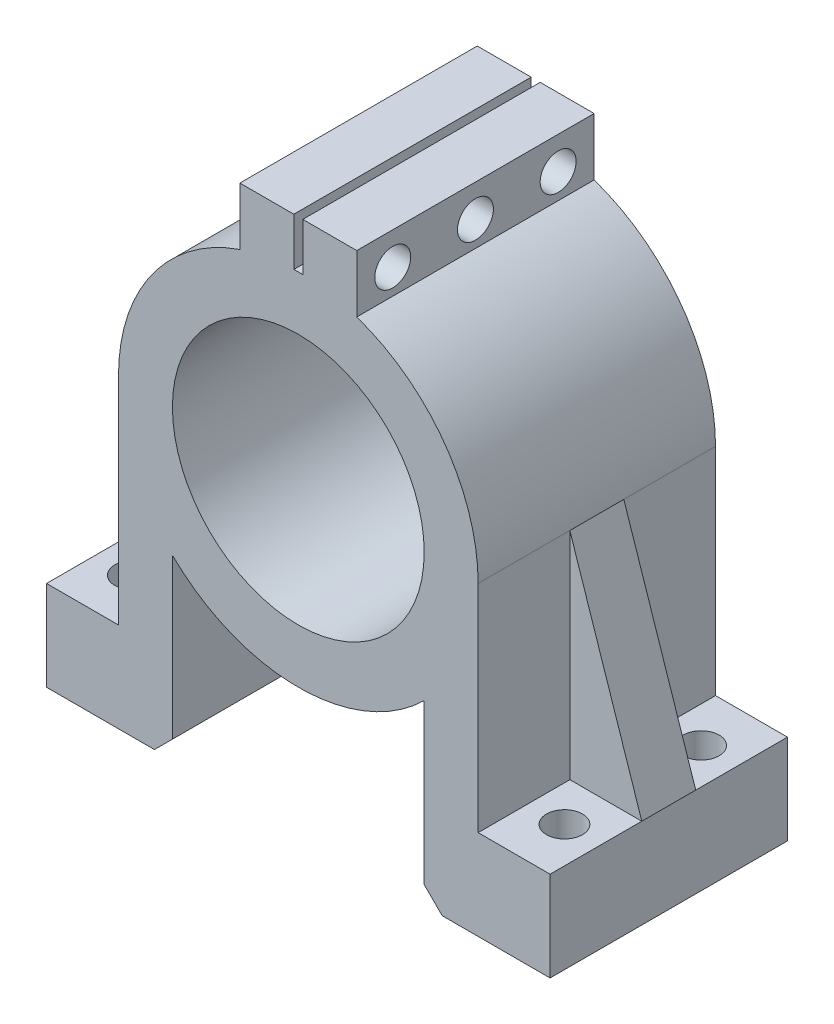
SolidWorks part; units mm, degrees
ref_plane "Front Plane" through (0, 0, 0) normal (0, 0, 1) x (1, 0, 0)
ref_plane "Top Plane" through (0, 0, 0) normal (0, 1, 0) x (1, 0, 0)
ref_plane "Right Plane" through (0, 0, 0) normal (1, 0, 0) x (0, 0, -1)
sketch "Sketch1" plane through (0, 0, 0) normal (0, 0, 1) x (1, 0, 0)
  line L0 (-14, 0) -> (-14, 5)
  line L1 (-14, 5) -> (-10, 5)
  line L2 (-10, 5) -> (-10, 17)
  line L3 (-14, 0) -> (-7, 0)
  line L4 (-7, 0) -> (-7, 9.8586)
  line L5 (0, 0) -> (0, 36.0632) construction
  line L6 (10, 5) -> (10, 17)
  line L7 (7, 0) -> (7, 9.8586)
  line L8 (14, 0) -> (7, 0)
  line L9 (14, 5) -> (10, 5)
  line L10 (14, 0) -> (14, 5)
  line L11 (3.25, 29.6571) -> (0.25, 29.6571)
  line L12 (-3.25, 29.6571) -> (-0.25, 29.6571)
  line L13 (-3.25, 29.6571) -> (-3.25, 26.4571)
  line L15 (-0.25, 29.6571) -> (-0.25, 26.9969)
  line L16 (0.25, 29.6571) -> (0.25, 26.9969)
  line L17 (3.25, 29.6571) -> (3.25, 26.4571)
  arc A0 (-3.25, 26.4571) -> (-10, 17) centre (0, 17) ccw
  circle A1 centre (0, 17) radius 7
  arc A2 (0.25, 26.9969) -> (-0.25, 26.9969) centre (0, 17) ccw
  arc A3 (-7, 9.8586) -> (7, 9.8586) centre (0, 17) ccw
  arc A4 (10, 17) -> (3.25, 26.4571) centre (0, 17) ccw
  dimension "D1" = 20
  dimension "D2" = 14
  dimension "D3" = 5
  dimension "D4" = 28
  dimension "D5" = 17
  dimension "D6" = 14
  dimension "D7" = 0.5
  dimension "D8" = 3.2
  dimension "D9" = 3
extrude "Boss-Extrude1" add sketch "Sketch1" along normal blind 13.2
hole_wizard "Hole1" positions "Sketch2" profile "Sketch3" legacy
sketch "Sketch2" plane through (3.25, 0, 0) normal (1, 0, 0) x (0, 0, -1)
  line L0 (-13.2, 26.4571) -> (-13.2, 29.6571) construction
  line L1 (-13.2, 26.4571) -> (0, 26.4571) construction
  line L2 (0, 26.4571) -> (0, 29.6571) construction
  line L3 (-6.6, 0) -> (-6.6, 27.8571) construction
  line L4 (-13.2, 0) -> (0, 0) construction
  point P0 (-11.2, 27.8571)
  point P2 (-2, 27.8571)
  point P11 (-6.6, 27.8571)
  point P20 (-6.6, 27.3389)
  point P21 (-6.6, 28.0184)
  point P22 (0, 0)
  dimension "D1" = 2
  dimension "D2" = 1.4
  dimension "D3" = 2
  dimension "D4" = 1.4
sketch "Sketch3" plane through (3.25, 27.8571, 11.2) normal (0, 1, 0) x (0, 0, -1)
  line L0 (0, 0) -> (0, 30)
  line L1 (0, 30) -> (1, 30)
  line L2 (1, 30) -> (1, 0)
  line L3 (1, 0) -> (0, 0)
  line L4 (0, 110) -> (0, -10) construction
  dimension "Diameter" = 2
  dimension "Depth" = 30
hole_wizard "Hole2" positions "Sketch4" profile "Sketch5" legacy
sketch "Sketch4" plane through (0, 5, 0) normal (0, 1, 0) x (1, 0, 0)
  line L0 (14, 0) -> (10, 0) construction
  line L1 (14, -13.2) -> (14, 0) construction
  line L2 (14, -13.2) -> (10, -13.2) construction
  point P0 (12, -2.8)
  point P2 (12, -10.4)
  dimension "D1" = 2.8
  dimension "D2" = 2
  dimension "D3" = 2
  dimension "D4" = 2.8
sketch "Sketch5" plane through (12, 5, 2.8) normal (1, 0, 0) x (0, 0, 1)
  line L0 (0, 0) -> (0, 30)
  line L1 (0, 30) -> (1, 30)
  line L2 (1, 30) -> (1, 0)
  line L3 (1, 0) -> (0, 0)
  line L4 (0, 110) -> (0, -10) construction
  dimension "Diameter" = 2
  dimension "Depth" = 30
mirror "Mirror1" about plane through (0, 0, 0) normal (1, 0, 0) of "Hole2"
ref_plane "Plane1" through (0, 0, 6.6) normal (0, 0, 1) x (1, 0, 0)
sketch "Sketch6" plane through (0, 0, 6.6) normal (0, 0, 1) x (1, 0, 0)
  line L0 (10, 17) -> (14, 5)
  line L1 (10, 5) -> (10, 17) construction
  line L2 (14, 5) -> (10, 5)
  line L3 (10, 5) -> (10, 17)
  line L4 (7, 0) -> (14, 0) construction
  dimension "D1" = 17
extrude "Boss-Extrude2" add sketch "Sketch6" along normal mid plane 3
mirror "Mirror2" about plane through (0, 0, 0) normal (1, 0, 0) of "Boss-Extrude2"
chamfer "Chamfer1" distance 1 2 edges at (7, 0, 6.6) (-7, 0, 6.6)
